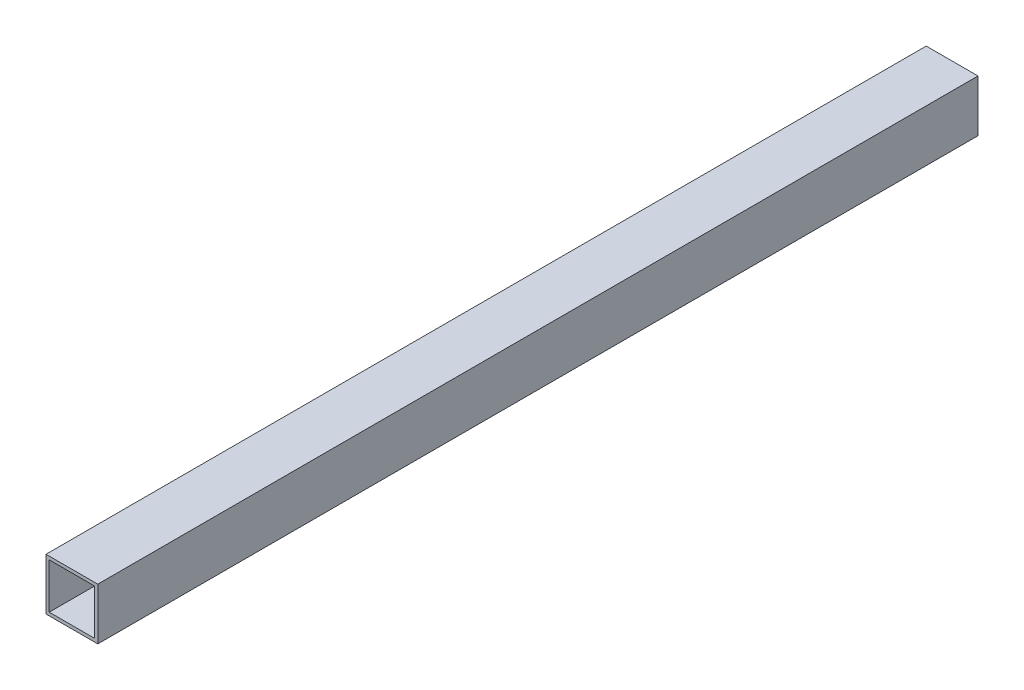
SolidWorks part; units mm, degrees
ref_plane "Front Plane" through (0, 0, 0) normal (0, 0, 1) x (1, 0, 0)
ref_plane "Top Plane" through (0, 0, 0) normal (0, 1, 0) x (1, 0, 0)
ref_plane "Right Plane" through (0, 0, 0) normal (1, 0, 0) x (0, 0, -1)
sketch "Sketch1" plane through (0, 0, 0) normal (0, 0, 1) x (1, 0, 0)
  line L1 (-25.4, -25.4) -> (25.4, -25.4)
  line L2 (-25.4, -25.4) -> (-25.4, 25.4)
  line L3 (-25.4, 25.4) -> (25.4, 25.4)
  line L4 (25.4, -25.4) -> (25.4, 25.4)
  line L5 (-25.4, -25.4) -> (25.4, 25.4) construction
  line L6 (-25.4, 25.4) -> (25.4, -25.4) construction
  point P0 (0, 0)
  dimension "D1" = 50.8
  dimension "D2" = 50.8
extrude "Boss-Extrude1" add sketch "Sketch1" along normal blind 863.6
shell "Shell1" thickness 3.175
